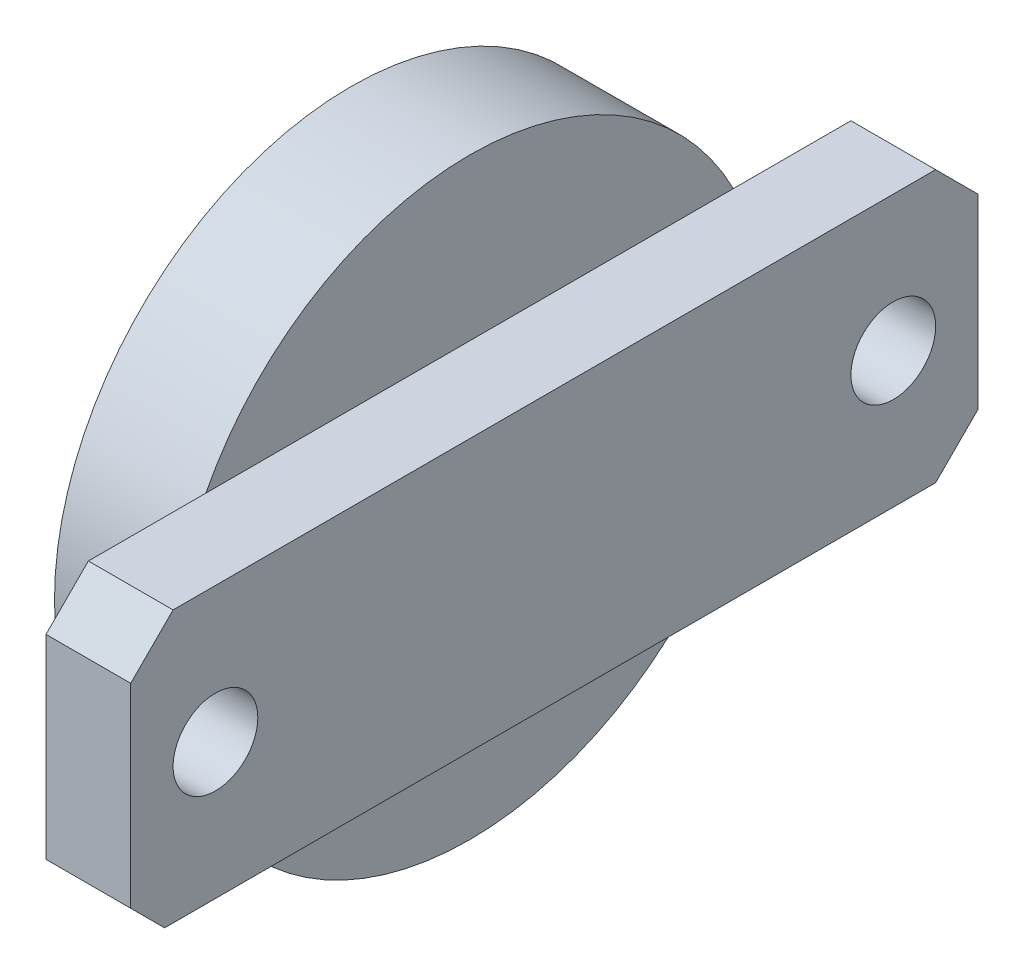
SolidWorks part; units mm, degrees
ref_plane "Front Plane" through (0, 0, 0) normal (0, 0, 1) x (1, 0, 0)
ref_plane "Top Plane" through (0, 0, 0) normal (0, 1, 0) x (1, 0, 0)
ref_plane "Right Plane" through (0, 0, 0) normal (1, 0, 0) x (0, 0, -1)
ref_plane "Plane1" through (5, 0, 0) normal (1, 0, 0) x (0, 0, -1)
sketch "Sketch1" plane through (5, 0, 0) normal (1, 0, 0) x (0, 0, -1)
  line L0 (25, -8) -> (25, 8)
  line L1 (25, 8) -> (-25, 8)
  line L2 (-25, 8) -> (-25, -8)
  line L3 (-25, -8) -> (25, -8)
extrude "Boss-Extrude1" add sketch "Sketch1" against normal blind 5
ref_plane "Plane2" through (0, 0, 0) normal (0, 0, -1) x (-1, 0, 0)
sketch "Sketch2" plane through (0, 0, 0) normal (0, 0, -1) x (-1, 0, 0)
  line L0 (0, 14) -> (0, 0)
  line L1 (0, 0) -> (7, 0)
  line L2 (7, 0) -> (7, 14)
  line L3 (7, 14) -> (0, 14)
  line L4 (0, 0) -> (7, 0) construction
revolve "Revolve1" add sketch "Sketch2" angle 360 about L4
hole_wizard "Ø5.0 (5) Diameter Hole1" positions "Sketch4" profile "Sketch3" hole size "Ø5.0" standard "ANSI Metric"
sketch "Sketch4" plane through (5, 0, 0) normal (1, 0, 0) x (0, 0, -1)
  point P0 (-20, 0)
  point P1 (20, 0)
sketch "Sketch3" plane through (5, 0, 20) normal (0, 1, 0) x (0, 0, -1)
  line L0 (0, 0) -> (0, 12)
  line L1 (0, 12) -> (2.5, 12)
  line L2 (2.5, 12) -> (2.5, 0)
  line L5 (2.5, 0) -> (0, 0)
  line L11 (0, -6.35) -> (0, 107.95) construction
  dimension "Thru Hole Dia." = 5
  dimension "Thru Hole Depth" = 12
chamfer "Chamfer1" distance 2.5 angle 45 3 edges at (2.5, 8, -25) (2.5, -8, -25) (2.5, 8, 25)
chamfer "Chamfer2" distance 2 angle 45 1 edges at (2.5, -8, 25)
sketch "Sketch5" plane through (-7, 0, 0) normal (-1, 0, 0) x (0, 0, 1)
  circle A0 centre (0, 0) radius 17.5
  dimension "D1" = 35
extrude "Boss-Extrude2" add sketch "Sketch5" against normal blind 7 contours A0
